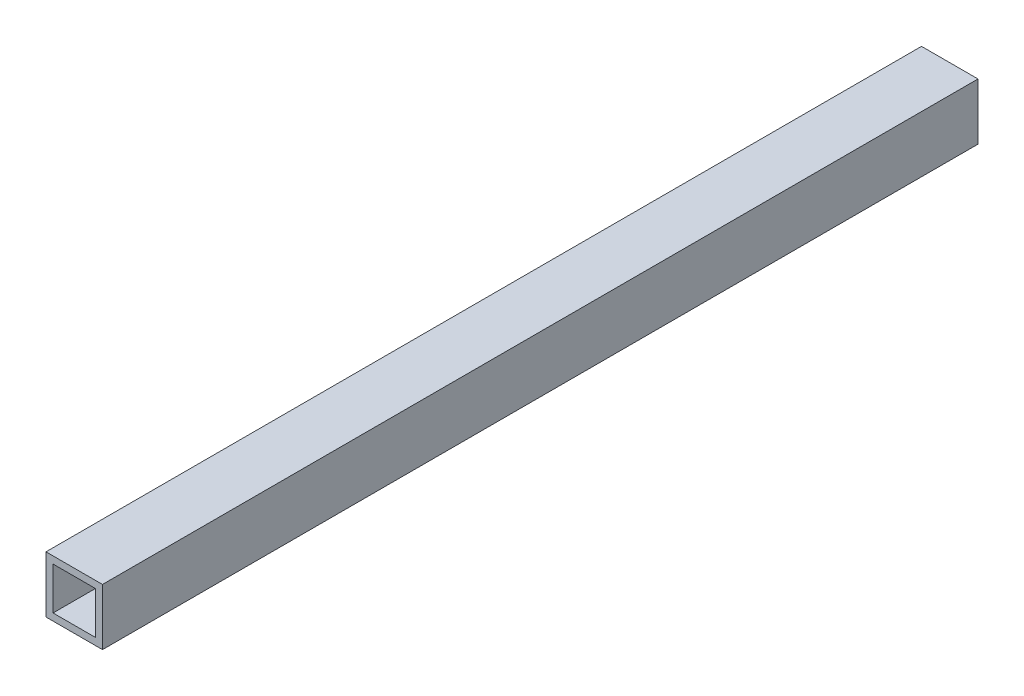
SolidWorks part; units mm, degrees
material "6063-O"
ref_plane "Front Plane" through (0, 0, 0) normal (0, 0, 1) x (1, 0, 0)
ref_plane "Top Plane" through (0, 0, 0) normal (0, 1, 0) x (1, 0, 0)
ref_plane "Right Plane" through (0, 0, 0) normal (1, 0, 0) x (0, 0, -1)
sketch "Sketch1" plane through (0, 0, 0) normal (0, 0, 1) x (1, 0, 0)
  line L1 (12.7, -12.7) -> (-12.7, -12.7)
  line L2 (12.7, -12.7) -> (12.7, 12.7)
  line L3 (12.7, 12.7) -> (-12.7, 12.7)
  line L4 (-12.7, -12.7) -> (-12.7, 12.7)
  line L5 (12.7, -12.7) -> (-12.7, 12.7) construction
  line L6 (12.7, 12.7) -> (-12.7, -12.7) construction
  line L7 (9.525, -9.525) -> (-9.525, -9.525)
  line L8 (9.525, -9.525) -> (9.525, 9.525)
  line L9 (9.525, 9.525) -> (-9.525, 9.525)
  line L10 (-9.525, -9.525) -> (-9.525, 9.525)
  line L11 (9.525, -9.525) -> (-9.525, 9.525) construction
  line L12 (9.525, 9.525) -> (-9.525, -9.525) construction
  point P0 (0, 0)
  point P6 (0, 0)
  dimension "D1" = 25.4
  dimension "D2" = 3.175
extrude "Boss-Extrude1" add sketch "Sketch1" along normal mid plane 393.7
